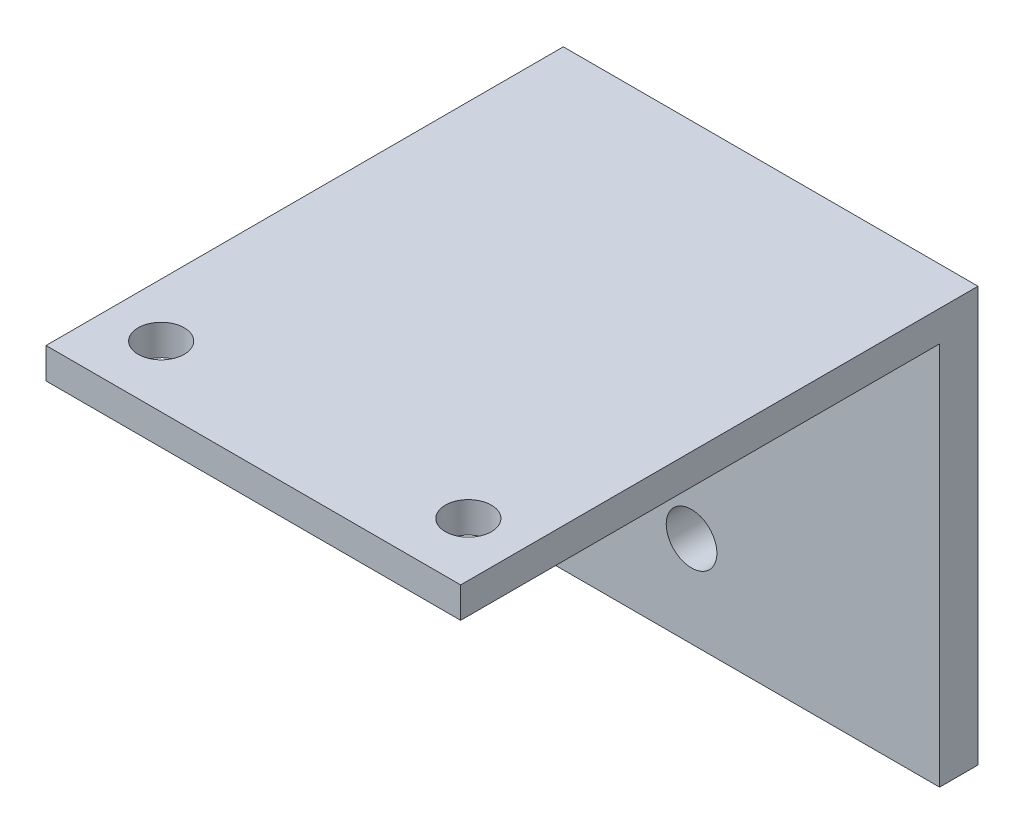
SolidWorks part; units mm, degrees
ref_plane "Plan de face" through (0, 0, 0) normal (0, 0, 1) x (1, 0, 0)
ref_plane "Plan de dessus" through (0, 0, 0) normal (0, 1, 0) x (1, 0, 0)
ref_plane "Plan de droite" through (0, 0, 0) normal (1, 0, 0) x (0, 0, -1)
sketch "Esquisse1" plane through (0, 0, 0) normal (0, 0, 1) x (1, 0, 0)
  line L1 (-27, -27) -> (27, -27)
  line L2 (-27, -27) -> (-27, 27)
  line L3 (-27, 27) -> (27, 27)
  line L4 (27, -27) -> (27, 27)
  line L5 (-27, -27) -> (27, 27) construction
  line L6 (-27, 27) -> (27, -27) construction
  line L7 (9, -27) -> (-9, -27)
  line L8 (9, -27) -> (9, 27)
  line L9 (9, 27) -> (-9, 27)
  line L10 (-9, -27) -> (-9, 27)
  line L11 (9, -27) -> (-9, 27) construction
  line L12 (9, 27) -> (-9, -27) construction
  circle A0 centre (-3.2581, 19) radius 3
  circle A1 centre (-3.2581, -21) radius 3
  point P0 (0, 0)
  point P7 (0, 0)
  dimension "D4" = 6
  dimension "D1" = 54
  dimension "D2" = 54
  dimension "D3" = 18
  dimension "D5" = 8
  dimension "D6" = 5.7419
  dimension "D7" = 2
extrude "Boss.-Extru.1" add sketch "Esquisse1" along normal blind 67.37 contours L8 L1 L4 L3 | L1 L10 L3 L2 | L10 L1 L8 L3 A1 A0
sketch "Esquisse2" plane through (0, 0, 67.37) normal (0, 0, 1) x (1, 0, 0)
  line L8 (23, 23) -> (-23, 23)
  line L9 (-23, 23) -> (-23, -23)
  line L10 (-23, -23) -> (23, -23)
  line L11 (23, -23) -> (23, 23)
  line L12 (38.775, 23) -> (-47.1129, 23)
  line L13 (-47.1129, 23) -> (-47.1129, -35.7903)
  line L14 (-47.1129, -35.7903) -> (38.775, -35.7903)
  line L15 (38.775, -35.7903) -> (38.775, 23)
  dimension "D1" = 4
extrude "Enlèv. mat.-Extru.1" cut sketch "Esquisse2" against normal blind 62.37
sketch "Esquisse3" plane through (0, 23, 0) normal (0, -1, 0) x (1, 0, 0)
  line L0 (27, 67.37) -> (-27, 67.37) construction
  line L1 (-27, 67.37) -> (-27, 5) construction
  circle A0 centre (-20, 59.37) radius 3
  circle A1 centre (20, 59.37) radius 3
  dimension "D3" = 6
  dimension "D1" = 8
  dimension "D2" = 7
  dimension "D4" = 2
extrude "Enlèv. mat.-Extru.2" cut sketch "Esquisse3" against normal blind 62.37
hole_wizard "Dégagement M61" positions "Esquisse5" profile "Esquisse4" hole size "M6" standard "JIS" end condition through all
sketch "Esquisse5" plane through (0, 0, 0) normal (0, 0, -1) x (-1, 0, 0)
  point P0 (5.3031, 16.5)
  point P2 (5.3031, -15.1245)
sketch "Esquisse4" plane through (-5.3031, 16.5, 0) normal (1, 0, 0) x (0, 1, 0)
  line L0 (0, 0) -> (0, 67.37)
  line L1 (0, 67.37) -> (3.3, 67.37)
  line L2 (3.3, 67.37) -> (3.3, 0)
  line L5 (3.3, 0) -> (0, 0)
  line L11 (0, -6.35) -> (0, 107.95) construction
  dimension "Diamètre du perçage jusqu'au prochain" = 6.6
  dimension "Profondeur du perçage jusqu'au prochain" = 67.37
